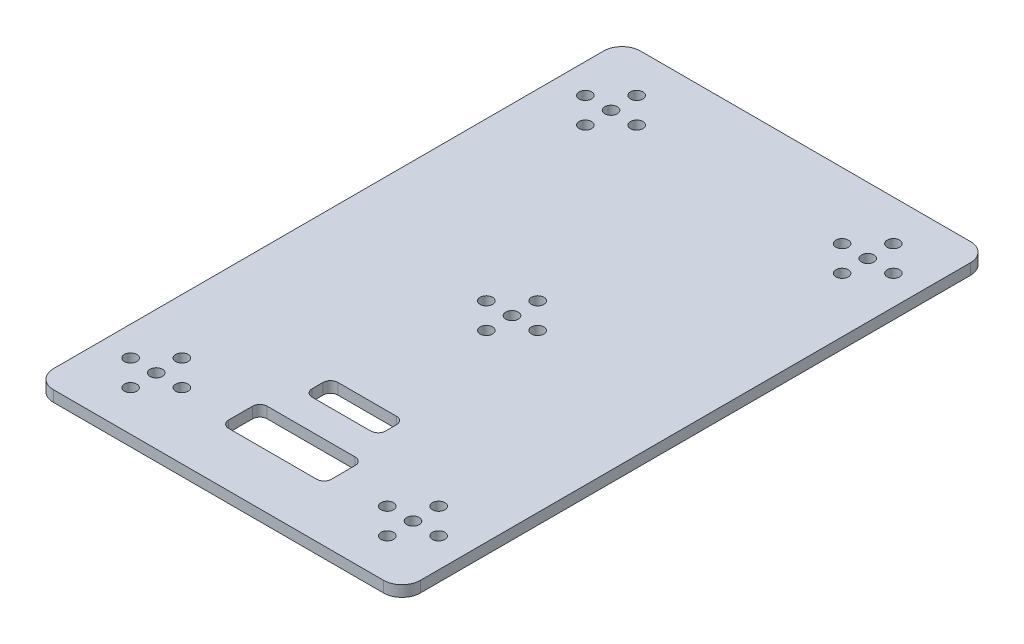
SolidWorks part; units mm, degrees
ref_plane "Front Plane" through (0, 0, 0) normal (0, 0, 1) x (1, 0, 0)
ref_plane "Top Plane" through (0, 0, 0) normal (0, 1, 0) x (1, 0, 0)
ref_plane "Right Plane" through (0, 0, 0) normal (1, 0, 0) x (0, 0, -1)
sketch "Sketch1" plane through (0, 0, 0) normal (0, 1, 0) x (1, 0, 0)
  line L1 (-50, -80) -> (50, -80)
  line L2 (-50, -80) -> (-50, 80)
  line L3 (-50, 80) -> (50, 80)
  line L4 (50, -80) -> (50, 80)
  line L5 (-50, -80) -> (50, 80) construction
  line L6 (-50, 80) -> (50, -80) construction
  point P0 (0, 0)
  dimension "D1" = 160
  dimension "D2" = 100
extrude "Boss-Extrude1" add sketch "Sketch1" along normal blind 3
hole_wizard "M3 Clearance Hole1" positions "Sketch2" profile "Sketch3" hole size "M3" standard "ISO" end condition up to next
sketch "Sketch2" plane through (0, 3, 0) normal (0, 1, 0) x (1, 0, 0)
  point P0 (-35, 62)
  point P3 (-35, 69)
  point P6 (-42, 62)
  point P9 (-35, 55)
  point P12 (-28, 62)
  point P15 (35, 69)
  point P18 (28, 62)
  point P21 (35, 62)
  point P24 (42, 62)
  point P27 (35, 55)
  point P30 (-35, -62)
  point P33 (-42, -62)
  point P36 (-35, -55)
  point P39 (-28, -62)
  point P42 (-35, -69)
  point P45 (35, -62)
  point P48 (35, -55)
  point P51 (28, -62)
  point P54 (42, -62)
  point P57 (35, -69)
sketch "Sketch3" plane through (-35, 3, -62) normal (1, 0, 0) x (0, 0, 1)
  line L0 (0, 0) -> (0, 3)
  line L1 (0, 3) -> (1.7, 3)
  line L2 (1.7, 3) -> (1.7, 0)
  line L5 (1.7, 0) -> (0, 0)
  line L11 (0, -6.35) -> (0, 107.95) construction
  dimension "Thru Hole Dia." = 3.4
  dimension "Thru Hole Depth" = 3
hole_wizard "M3 Clearance Hole2" positions "Sketch4" profile "Sketch5" hole size "M3" standard "ISO" end condition up to next
sketch "Sketch4" plane through (0, 3, 0) normal (0, 1, 0) x (1, 0, 0)
  point P0 (0, 0)
  point P3 (0, 7)
  point P6 (7, 0)
  point P9 (0, -7)
  point P12 (-7, 0)
sketch "Sketch5" plane through (0, 3, 0) normal (1, 0, 0) x (0, 0, 1)
  line L0 (0, 0) -> (0, 3)
  line L1 (0, 3) -> (1.7, 3)
  line L2 (1.7, 3) -> (1.7, 0)
  line L5 (1.7, 0) -> (0, 0)
  line L11 (0, -6.35) -> (0, 107.95) construction
  dimension "Thru Hole Dia." = 3.4
  dimension "Thru Hole Depth" = 3
sketch "Sketch6" plane through (0, 3, 0) normal (0, 1, 0) x (1, 0, 0)
  line L0 (0, -40) -> (0, -80) construction
  line L1 (14, -65.25) -> (-14, -65.25)
  line L2 (14, -65.25) -> (14, -54.75)
  line L3 (14, -54.75) -> (-14, -54.75)
  line L4 (-14, -65.25) -> (-14, -54.75)
  line L5 (14, -65.25) -> (-14, -54.75) construction
  line L6 (14, -54.75) -> (-14, -65.25) construction
  line L7 (-33.5, -40) -> (33.5, -40) construction
  line L8 (-50, -80) -> (50, -80) construction
  line L10 (-10, -46.5) -> (10, -46.5)
  line L11 (-10, -46.5) -> (-10, -39.5)
  line L12 (-10, -39.5) -> (10, -39.5)
  line L13 (10, -46.5) -> (10, -39.5)
  line L14 (-10, -46.5) -> (10, -39.5) construction
  line L15 (-10, -39.5) -> (10, -46.5) construction
  point P0 (0, -60)
  point P12 (0, -43)
  dimension "D1" = 28
  dimension "D2" = 10.5
  dimension "D3" = 7
  dimension "D4" = 20
  dimension "D5" = 3
extrude "Cut-Extrude1" cut sketch "Sketch6" against normal up to next
fillet "Fillet1" radius 5 4 edges at (-50, 1.5, -80) (50, 1.5, -80) (50, 1.5, 80) (-50, 1.5, 80)
fillet "Fillet2" radius 2 8 edges at (14, 1.5, 65.25) (-14, 1.5, 65.25) (-14, 1.5, 54.75) (14, 1.5, 54.75) (10, 1.5, 46.5) (-10, 1.5, 46.5) (10, 1.5, 39.5) (-10, 1.5, 39.5)
